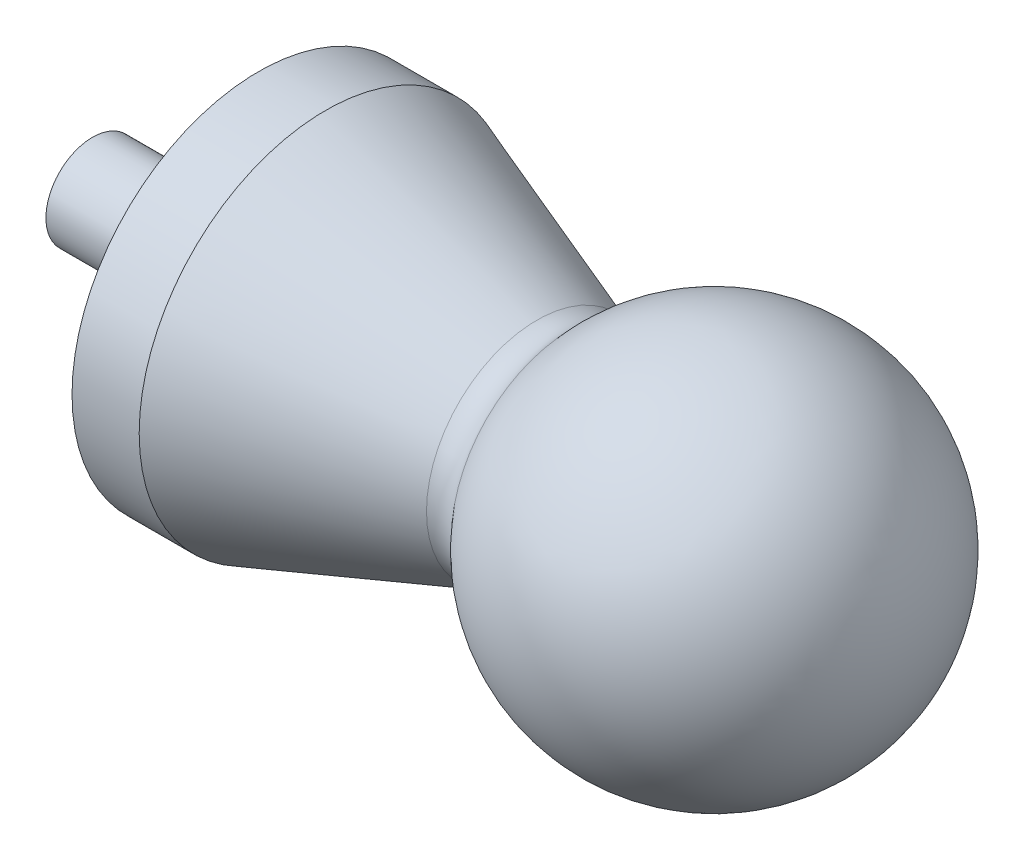
SolidWorks part; units mm, degrees
material "Brass"
ref_plane "Front" through (0, 0, 0) normal (0, 0, 1) x (1, 0, 0)
ref_plane "Top" through (0, 0, 0) normal (0, 1, 0) x (1, 0, 0)
ref_plane "Right" through (0, 0, 0) normal (1, 0, 0) x (0, 0, -1)
sketch "Sketch1" plane through (0, 0, 0) normal (0, 1, 0) x (1, 0, 0)
  line L0 (-50, 0) -> (50, 0) construction
  line L1 (0, 0) -> (-40, 0) construction
  line L2 (0, 0) -> (0, 3) construction
  line L3 (0, 3) -> (-40, 3) construction
  line L4 (-40, 0) -> (-40, 3) construction
  line L5 (25.0028, 0) -> (-54.8539, 0) construction
  line L6 (0, 0) -> (-25, 0) construction
  line L7 (0, 0) -> (0, 12) construction
  line L8 (0, 12) -> (-25, 12) construction
  line L9 (-25, 0) -> (-25, 12) construction
  line L10 (-25, 12) -> (-10.0178, 6.6064)
  line L11 (-40, 0) -> (-40, 3)
  line L12 (-25, 12) -> (-29.32, 12) construction
  line L13 (-25, 12) -> (-25, 0) construction
  line L14 (-25, 0) -> (-29.32, 0) construction
  line L15 (-29.32, 12) -> (-29.32, 0) construction
  line L16 (-40, 3) -> (-29.32, 3)
  line L17 (-29.32, 3) -> (-29.32, 12)
  line L18 (-29.32, 12) -> (-25, 12)
  line L19 (-40, 0) -> (12, 0)
  arc A0 (12, 0) -> (-10.0178, 6.6064) centre (0, 0) ccw
revolve "Revolve1" add sketch "Sketch1" angle 360 about L5
fillet "Fillet1" radius 2 1 edges at (-10.0178, 0, -6.6064)
